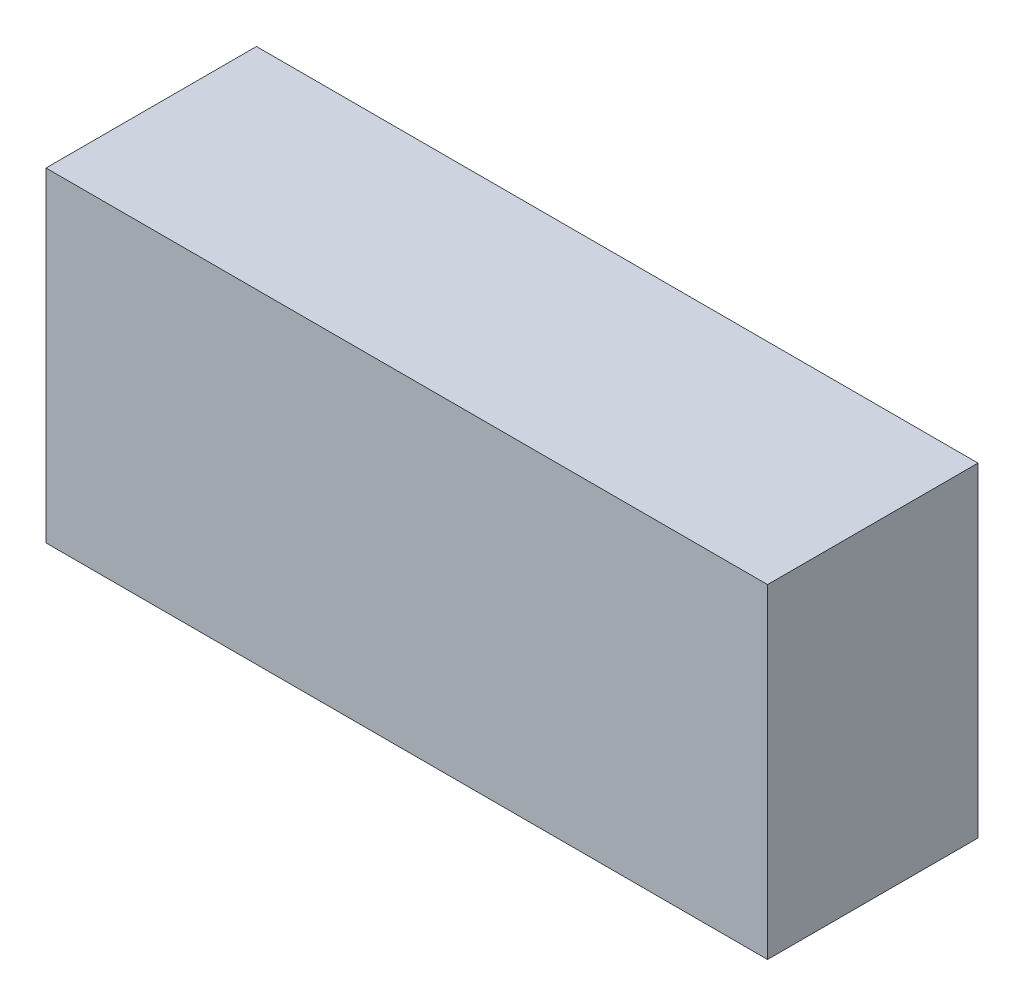
SolidWorks part; units mm, degrees
ref_plane "Front Plane" through (0, 0, 0) normal (0, 0, 1) x (1, 0, 0)
ref_plane "Top Plane" through (0, 0, 0) normal (0, 1, 0) x (1, 0, 0)
ref_plane "Right Plane" through (0, 0, 0) normal (1, 0, 0) x (0, 0, -1)
sketch "Sketch1" plane through (0, 0, 0) normal (0, 1, 0) x (1, 0, 0)
  line L1 (-73.0528, -33.4855) -> (46.9472, -33.4855)
  line L2 (-73.0528, -33.4855) -> (-73.0528, 1.5145)
  line L3 (-73.0528, 1.5145) -> (46.9472, 1.5145)
  line L4 (46.9472, -33.4855) -> (46.9472, 1.5145)
  dimension "D1" = 120
  dimension "D2" = 35
extrude "Boss-Extrude1" add sketch "Sketch1" along normal blind 54
ref_plane "Plane1" through (0, 0, 15.9855) normal (0, 0, -1) x (-1, 0, 0)
